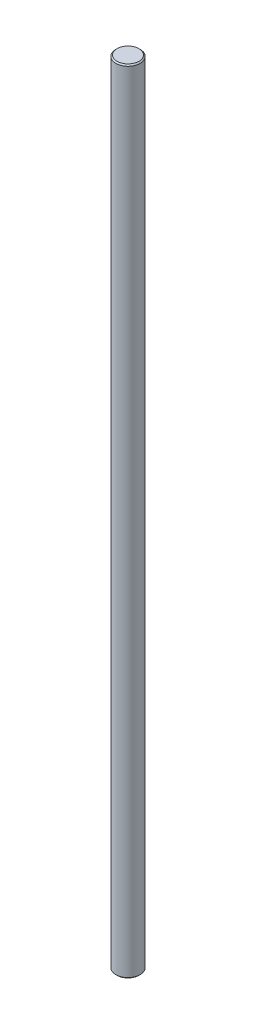
SolidWorks part; units mm, degrees
ref_plane "Front Plane" through (0, 0, 0) normal (0, 0, 1) x (1, 0, 0)
ref_plane "Top Plane" through (0, 0, 0) normal (0, 1, 0) x (1, 0, 0)
ref_plane "Right Plane" through (0, 0, 0) normal (1, 0, 0) x (0, 0, -1)
sketch "Sketch1" plane through (0, 0, 0) normal (0, 1, 0) x (1, 0, 0)
  circle A0 centre (0, 0) radius 10
  dimension "D1" = 20
extrude "Boss-Extrude1" add sketch "Sketch1" along normal blind 650
chamfer "Chamfer1" distance 1 angle 45 2 edges at (0, 650, 10) (0, 0, 10)
